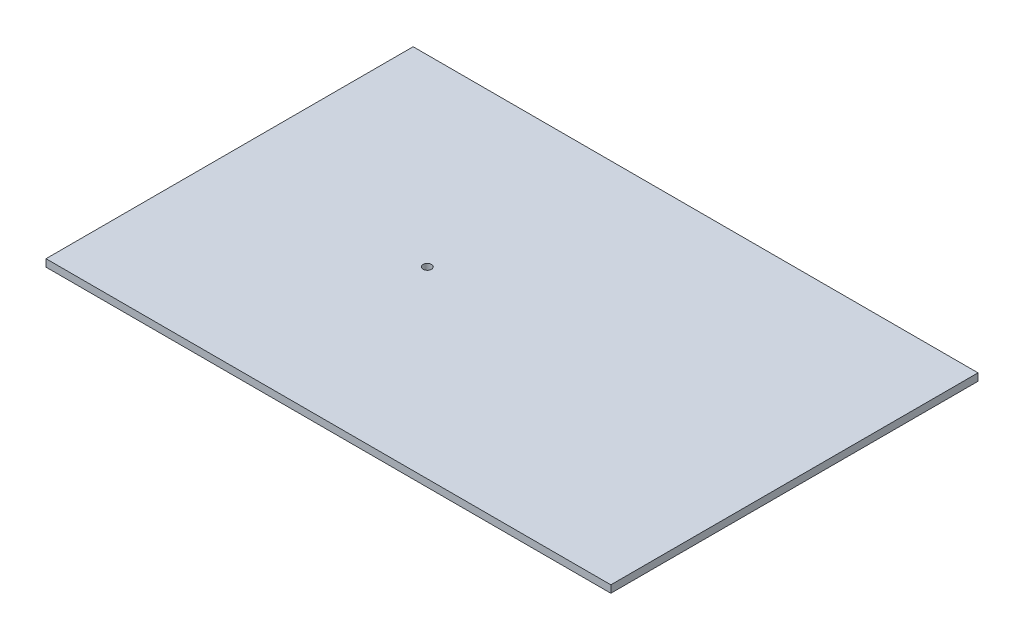
SolidWorks part; units mm, degrees
ref_plane "Front Plane" through (0, 0, 0) normal (0, 0, 1) x (1, 0, 0)
ref_plane "Top Plane" through (0, 0, 0) normal (0, 1, 0) x (1, 0, 0)
ref_plane "Right Plane" through (0, 0, 0) normal (1, 0, 0) x (0, 0, -1)
sketch "Sketch2" plane through (0, 0, 0) normal (0, 1, 0) x (1, 0, 0)
  line L1 (-127, -82.55) -> (127, -82.55)
  line L2 (-127, -82.55) -> (-127, 82.55)
  line L3 (-127, 82.55) -> (127, 82.55)
  line L4 (127, -82.55) -> (127, 82.55)
  line L5 (-127, -82.55) -> (127, 82.55) construction
  line L6 (-127, 82.55) -> (127, -82.55) construction
  line L7 (-127, 82.55) -> (-38.1, 82.55)
  line L8 (-127, 82.55) -> (-127, 0)
  line L9 (-127, 0) -> (-38.1, 0)
  line L10 (-38.1, 82.55) -> (-38.1, 0)
  circle A0 centre (-38.1, 0) radius 1.905
  point P0 (0, 0)
  dimension "D5" = 3.81
  dimension "D1" = 254
  dimension "D2" = 165.1
  dimension "D3" = 82.55
  dimension "D4" = 88.9
extrude "Boss-Extrude1" add sketch "Sketch2" along normal blind 3.302 contours A0 L9 L2 L1 L4 L3 L10 | A0 L10 L3 L2 L9
